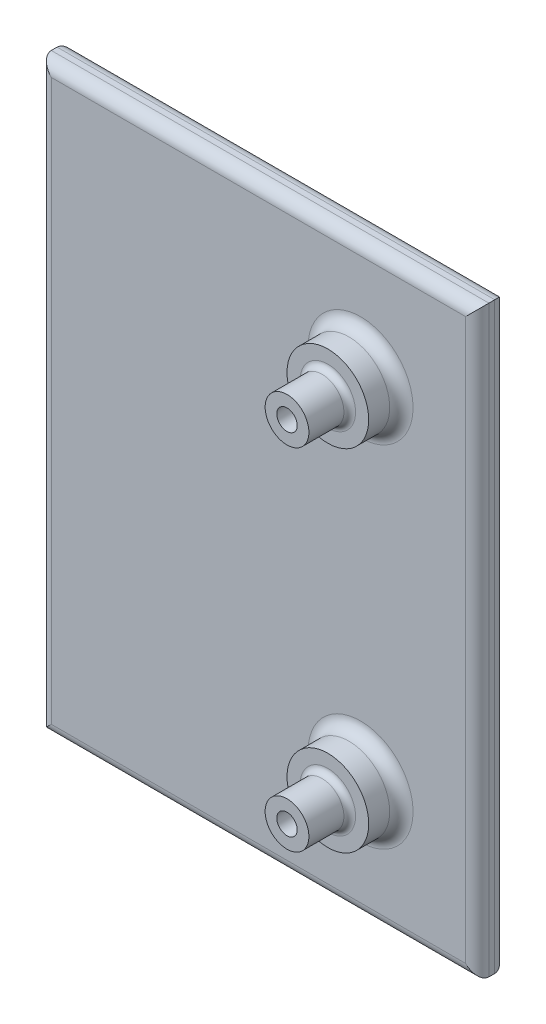
SolidWorks part; units mm, degrees
ref_plane "Front Plane" through (0, 0, 0) normal (1, 0, 0) x (0, 1, 0)
ref_plane "Top Plane" through (0, 0, 0) normal (0, 0, 1) x (0, 1, 0)
ref_plane "Right Plane" through (0, 0, 0) normal (0, 1, 0) x (-1, 0, 0)
sketch "Sketch1" plane through (0, 0, 0) normal (0, 0, 1) x (0, 1, 0)
  line L1 (0, 0) -> (100, 0)
  line L2 (0, 0) -> (0, 75)
  line L3 (0, 75) -> (100, 75)
  line L4 (100, 0) -> (100, 75)
  dimension "D1" = 100
  dimension "D2" = 75
extrude "Plate" add sketch "Sketch1" along normal blind 5
sketch "Sketch5" plane through (0, 0, 5) normal (0, 0, 1) x (1, 0, 0)
  line L0 (-75, 50) -> (0, 50) construction
  line L3 (-75, 100) -> (-75, 0) construction
  line L4 (0, 0) -> (0, 100) construction
sketch "Sketch2" plane through (0, 0, 5) normal (0, 0, 1) x (1, 0, 0)
  line L1 (-75, 0) -> (0, 0) construction
  line L2 (0, 0) -> (0, 100) construction
  circle A0 centre (-20, 20) radius 7
  dimension "D2" = 14
  dimension "D1" = 20
  dimension "D3" = 20
extrude "Bearing Support" add sketch "Sketch2" along normal blind 5.6 contours A0
sketch "Sketch3" plane through (0, 0, 10.6) normal (0, 0, 1) x (1, 0, 0)
  circle A0 centre (-20, 20) radius 3.75
  circle A1 centre (-20, 20) radius 7 construction
  dimension "D1" = 7.5
extrude "Bearing Pin" add sketch "Sketch3" along normal blind 7 contours A0
sketch "Sketch4" plane through (0, 0, 17.6) normal (0, 0, 1) x (1, 0, 0)
  circle A0 centre (-20, 20) radius 1.75
  circle A1 centre (-20, 20) radius 3.75 construction
  dimension "D1" = 3.5
extrude "Screw ThroughHole" cut sketch "Sketch4" against normal up to surface (17.6 mm away) contours A0 up to face at (-37.5, 50, 0)
ref_plane "Plane1" through (0, 50, 0) normal (0, -1, 0) x (-1, 0, 0)
mirror "Mirror1" about plane through (0, 50, 0) normal (0, -1, 0) of "Bearing Support", "Screw ThroughHole", "Bearing Pin"
fillet "Fillet1" radius 2 10 edges at (-27, 20, 5) (-13, 80, 5) (-37.5, 100, 0) (-37.5, 100, 5) (0, 50, 0) (0, 50, 5) (-37.5, 0, 0) (-37.5, 0, 5) (-75, 50, 0) (-75, 50, 5)
fillet "Fillet2" radius 1 2 edges at (-16.25, 80, 10.6) (-16.25, 20, 10.6)
